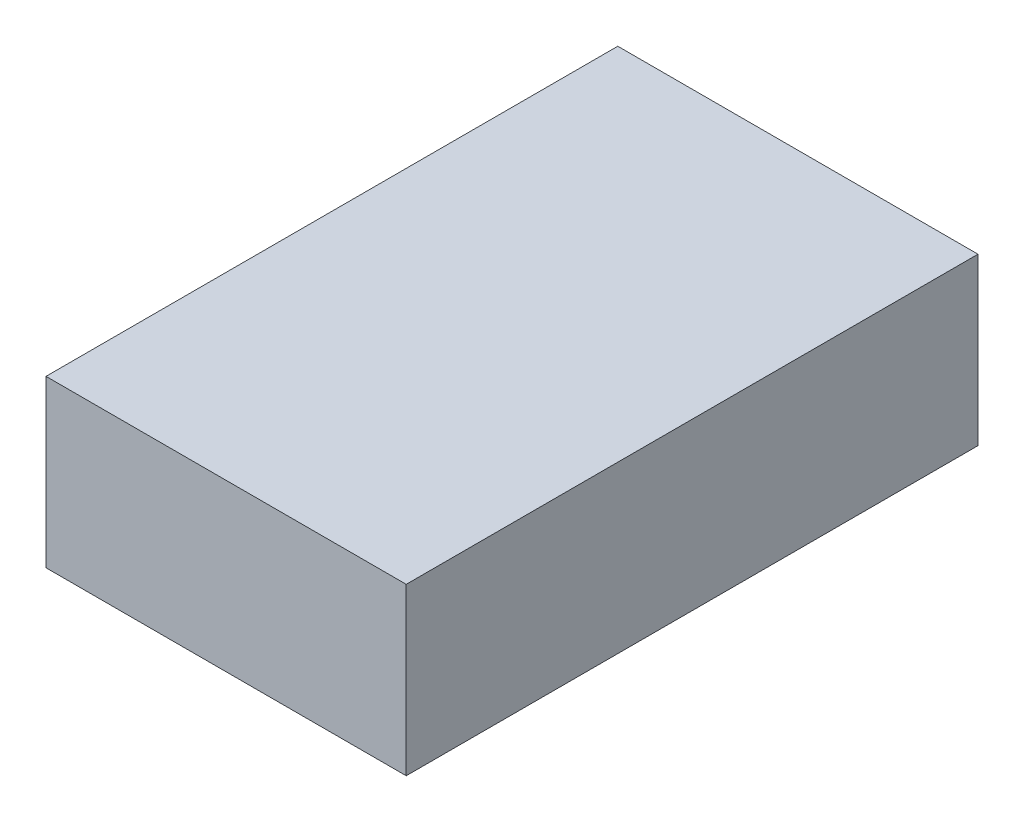
SolidWorks part; units mm, degrees
ref_plane "Ön Düzlem" through (0, 0, 0) normal (0, 0, 1) x (1, 0, 0)
ref_plane "Üst Düzlem" through (0, 0, 0) normal (0, 1, 0) x (1, 0, 0)
ref_plane "Sağ Düzlem" through (0, 0, 0) normal (1, 0, 0) x (0, 0, -1)
sketch "Çizim1" plane through (0, 0, 0) normal (0, 0, 1) x (1, 0, 0)
  line L1 (-13.3872, 8.5424) -> (18.1128, 8.5424)
  line L2 (-13.3872, 8.5424) -> (-13.3872, -5.9576)
  line L3 (-13.3872, -5.9576) -> (18.1128, -5.9576)
  line L4 (18.1128, 8.5424) -> (18.1128, -5.9576)
  dimension "D1" = 31.5
  dimension "D2" = 14.5
extrude "Yükseklik-Ekstrüzyon1" add sketch "Çizim1" along normal blind 50
